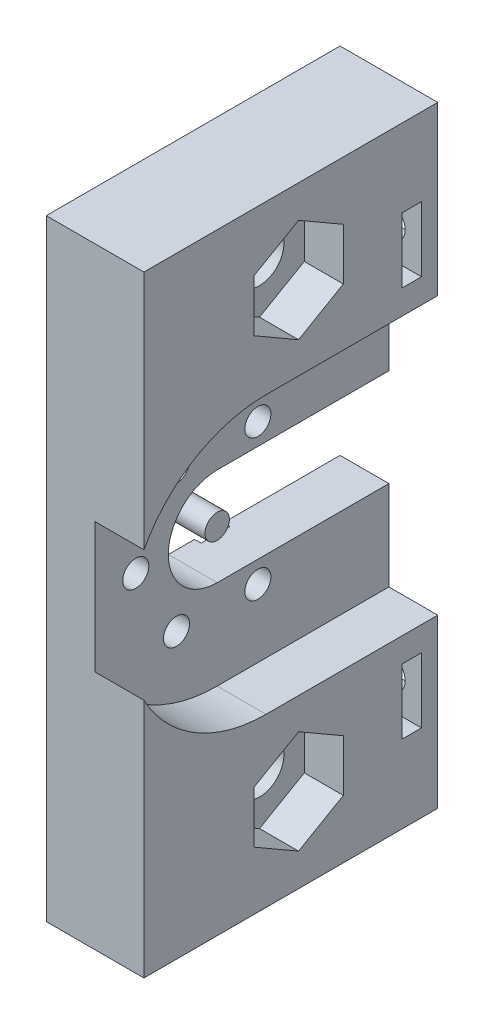
SolidWorks part; units mm, degrees
ref_plane "正面" through (0, 0, 0) normal (1, 0, 0) x (0, 1, 0)
ref_plane "平面" through (0, 0, 0) normal (0, 0, 1) x (0, 1, 0)
ref_plane "右側面" through (0, 0, 0) normal (0, 1, 0) x (-1, 0, 0)
sketch "ｽｹｯﾁ2" plane through (0, 0, 0) normal (1, 0, 0) x (0, 1, 0)
  line L5 (20, -7.5) -> (-20, -7.5)
  line L6 (20, -7.5) -> (20, 7.5)
  line L7 (20, 7.5) -> (-20, 7.5)
  line L8 (-20, -7.5) -> (-20, 7.5)
  line L9 (20, -7.5) -> (-20, 7.5) construction
  line L10 (20, 7.5) -> (-20, -7.5) construction
  point P0 (0, 0)
  dimension "D1" = 40
  dimension "D2" = 15
extrude "ﾎﾞｽ - 押し出し5" add sketch "ｽｹｯﾁ2" along normal mid plane 6
sketch "ｽｹｯﾁ10" plane through (3, 0, 0) normal (1, 0, 0) x (0, 1, 0)
  circle A0 centre (0, 0) radius 5 construction
  circle A1 centre (-4.3301, 2.5) radius 0.8
  circle A2 centre (4.3301, -2.5) radius 0.8
  circle A3 centre (0, 5) radius 0.8
  circle A4 centre (4.3301, 2.5) radius 0.8
  circle A5 centre (-4.3301, -2.5) radius 0.8
  dimension "D1" = 10
  dimension "D2" = 1.6
  dimension "D3" = 1.6
  dimension "D4" = 1.6
  dimension "D6" = 1.6
  dimension "D9" = 1.6
  dimension "D5" = 60
  dimension "D7" = 60
  dimension "D8" = 60
  dimension "D10" = 60
extrude "ｶｯﾄ - 押し出し2" cut sketch "ｽｹｯﾁ10" against normal through all contours A2 | A4 | A3 | A1 | A5
sketch "ｽｹｯﾁ11" plane through (3, 0, 0) normal (1, 0, 0) x (0, 1, 0)
  line L0 (-3, 0) -> (-3, -7.5)
  line L1 (20, -7.5) -> (-20, -7.5) construction
  line L2 (-3, -7.5) -> (3, -7.5)
  line L3 (3, -7.5) -> (3, 0)
  line L4 (3, 0) -> (-3, 0)
  circle A0 centre (0, 0) radius 5 construction
  circle A1 centre (0, 0) radius 3
  line M11 (-20, -7.5) -> (20, -7.5)
  dimension "D1" = 2
extrude "ｶｯﾄ - 押し出し3" cut sketch "ｽｹｯﾁ11" against normal through all contours A1 L0 L3 M11 | L4 A1 | L4 A1
sketch "ｽｹｯﾁ12" plane through (3, 0, 0) normal (1, 0, 0) x (0, 1, 0)
  circle A0 centre (0, 0) radius 8.5
  dimension "D1" = 17
extrude "ｶｯﾄ - 押し出し4" cut sketch "ｽｹｯﾁ12" against normal blind 3
sketch "ｽｹｯﾁ13" plane through (-3, 0, 0) normal (-1, 0, 0) x (0, -1, 0)
  circle A0 centre (0, 0) radius 5 construction
  circle A1 centre (-4.3301, -2.5) radius 1.6
  circle A2 centre (-4.3301, 2.5) radius 1.6
  circle A3 centre (0, 5) radius 1.6
  circle A4 centre (4.3301, 2.5) radius 1.6
  circle A5 centre (4.3301, -2.5) radius 1.6
  dimension "D1" = 3.2
  dimension "D2" = 3.2
  dimension "D3" = 3.2
  dimension "D4" = 3.2
  dimension "D5" = 3.2
  dimension "D6" = 120
  dimension "D7" = 60
  dimension "D8" = 60
extrude "ｶｯﾄ - 押し出し5" cut sketch "ｽｹｯﾁ13" against normal blind 0.4
sketch "ｽｹｯﾁ15" plane through (0, 0, 0) normal (1, 0, 0) x (0, 1, 0)
  circle A0 centre (0, 0) radius 0.75
  dimension "D1" = 1.5
extrude "ﾎﾞｽ - 押し出し6" add sketch "ｽｹｯﾁ15" against normal blind 3 separate body contours A0
sketch "ｽｹｯﾁ16" plane through (-3, 0, 0) normal (-1, 0, 0) x (0, -1, 0)
  line L0 (0, 0) -> (-23.3043, 0) construction
  circle A1 centre (0, 0) radius 3.25 construction
  circle A2 centre (-13.6038, -2) radius 10.5 construction
  circle A3 centre (13.6038, -2) radius 10.5 construction
  circle A4 centre (-13.6038, -2) radius 1.5
  circle A5 centre (13.6038, -2) radius 1.5
  dimension "D1" = 6.5
  dimension "D2" = 21
  dimension "D3" = 21
  dimension "D4" = 3
  dimension "D5" = 3
  dimension "D6" = 2
  dimension "D7" = 2
extrude "ｶｯﾄ - 押し出し6" cut sketch "ｽｹｯﾁ16" against normal through all contours A4 | A5
sketch "ｽｹｯﾁ18" plane through (-3, 0, 0) normal (-1, 0, 0) x (0, -1, 0)
  line L0 (0, 0) -> (-21.0487, 0) construction
  circle A0 centre (0, 0) radius 13.75 construction
  circle A1 centre (-13.6038, -2) radius 2.05
  circle A2 centre (13.6038, -2) radius 2.05
  dimension "D1" = 4.1
  dimension "D2" = 4.1
  dimension "D3" = 2
extrude "ｶｯﾄ - 押し出し8" cut sketch "ｽｹｯﾁ18" against normal blind 1
sketch "ｽｹｯﾁ19" plane through (3, 0, 0) normal (1, 0, 0) x (0, 1, 0)
  line L0 (0, 0) -> (2.6086, 0) construction
  line L1 (-10.4283, -2) -> (-12.0161, 0.75)
  line L2 (-12.0161, 0.75) -> (-15.1915, 0.75)
  line L3 (-15.1915, 0.75) -> (-16.7792, -2)
  line L4 (-16.7792, -2) -> (-15.1915, -4.75)
  line L5 (-15.1915, -4.75) -> (-12.0161, -4.75)
  line L6 (-12.0161, -4.75) -> (-10.4283, -2)
  line L7 (15.1915, 0.75) -> (12.0161, 0.75)
  line L8 (12.0161, 0.75) -> (10.4283, -2)
  line L9 (10.4283, -2) -> (12.0161, -4.75)
  line L10 (12.0161, -4.75) -> (15.1915, -4.75)
  line L11 (15.1915, -4.75) -> (16.7792, -2)
  line L12 (16.7792, -2) -> (15.1915, 0.75)
  circle A0 centre (0, 0) radius 13.75 construction
  circle A1 centre (-13.6038, -2) radius 2.75 construction
  circle A2 centre (13.6038, -2) radius 2.75 construction
  dimension "D1" = 5.5
  dimension "D2" = 5.5
  dimension "D3" = 2
  dimension "D4" = 2
extrude "ｶｯﾄ - 押し出し10" cut sketch "ｽｹｯﾁ19" against normal blind 2.4 contours L11 L12 L7 L8 L9 L10 | L1 L2 L3 L4 L5 L6
sketch "ｽｹｯﾁ21" plane through (3, 0, 0) normal (1, 0, 0) x (0, 1, 0)
  line L0 (0, 0) -> (-5.9571, 0) construction
  line L1 (-13.6038, -2) -> (-13.6038, -7.5) construction
  line L2 (20, -7.5) -> (-20, -7.5) construction
  circle A0 centre (0, 0) radius 3.25 construction
  circle A1 centre (-13.6038, -2) radius 10.5 construction
  circle A2 centre (-13.6038, -2) radius 11.75 construction
  circle A3 centre (13.6038, -2) radius 10.5 construction
  circle A4 centre (13.6038, -2) radius 11.75 construction
  dimension "D1" = 6.5
  dimension "D2" = 21
  dimension "D4" = 23.5
  dimension "D6" = 21
  dimension "D8" = 23.5
  dimension "D3" = 2
  dimension "D5" = 5.5
  dimension "D7" = 2
sketch "ｽｹｯﾁ23" plane through (0, 0, -7.5) normal (0, 0, -1) x (1, 0, 0)
  line L0 (-3, -3) -> (0, -3) construction
  line L6 (-3, 4.0776) -> (-3, 3)
  line L7 (-3, 3) -> (0, 3)
  line L8 (0, 4.0776) -> (0, 3)
  line L9 (-3, -3) -> (0, -3)
  line L10 (-3, -3) -> (-3, -4)
  line L12 (0, -3) -> (0, -4)
  line L13 (0, 4.0776) -> (3, 4.0776)
  line L15 (3, -4) -> (3, -20)
  line L16 (3, -20) -> (-3, -20)
  line L17 (-3, -4) -> (-3, -20)
  line L18 (3, 20) -> (-3, 20)
  line L19 (3, 20) -> (3, 4.0776)
  line L21 (-3, 20) -> (-3, 4.0776)
  line L22 (3, -4) -> (0, -4)
extrude "ﾎﾞｽ - 押し出し7" add sketch "ｽｹｯﾁ23" along normal blind 3.05
sketch "ｽｹｯﾁ22" plane through (3, 0, 0) normal (1, 0, 0) x (0, 1, 0)
  line L0 (-13.6038, -2) -> (-13.6038, -11.75)
  line L1 (-17.1626, -10.55) -> (-10.7729, -10.55) construction
  line L2 (-17.1626, -10.55) -> (-17.1626, -11.75) construction
  line L3 (-17.1626, -11.75) -> (-10.7729, -11.75) construction
  line L4 (-10.7729, -10.55) -> (-10.7729, -11.75) construction
  line L5 (-4.0776, -10.55) -> (-20, -10.55) construction
  line L6 (-13.6038, -11.75) -> (-13.6038, -13.75)
  circle A0 centre (-13.6038, -2) radius 11.75 construction
  dimension "D1" = 1.2
sketch "ｽｹｯﾁ24" plane through (0, -4.0776, 0) normal (0, 1, 0) x (-1, 0, 0)
  line L1 (-3, -7.5) -> (0, -7.5)
  line L2 (-3, -7.5) -> (-3, -10.55)
  line L3 (-3, -10.55) -> (0, -10.55)
  line L4 (0, -7.5) -> (0, -10.55)
extrude "ﾎﾞｽ - 押し出し8" add sketch "ｽｹｯﾁ24" along normal blind 1.08
sketch "ｽｹｯﾁ25" plane through (0, 4, 0) normal (0, -1, 0) x (1, 0, 0)
  line L1 (0, -7.5) -> (3, -7.5)
  line L2 (0, -7.5) -> (0, -10.55)
  line L3 (0, -10.55) -> (3, -10.55)
  line L4 (3, -7.5) -> (3, -10.55)
extrude "ﾎﾞｽ - 押し出し9" add sketch "ｽｹｯﾁ25" along normal blind 1
sketch "ｽｹｯﾁ26" plane through (3, 0, 0) normal (1, 0, 0) x (0, 1, 0)
  line L0 (20, -10.55) -> (3, -10.55) construction
  line L1 (-8.5, 0) -> (8.5, 0)
  line L2 (-8.5, 0) -> (-8.5, -10.55)
  line L3 (-8.5, -10.55) -> (8.5, -10.55)
  line L4 (8.5, 0) -> (8.5, -10.55)
  circle A0 centre (0, 0) radius 8.5
  dimension "D1" = 17
extrude "ｶｯﾄ - 押し出し11" cut sketch "ｽｹｯﾁ26" against normal blind 3 contours A0 | L2 L1 L4 L3
sketch "ｽｹｯﾁ28" plane through (3, 0, 0) normal (1, 0, 0) x (0, 1, 0)
  line L0 (-8.5, -10.55) -> (-20, -10.55) construction
  line L1 (-20, 7.5) -> (-18.7792, 7.5)
  line L2 (-20, 7.5) -> (-20, -10.55)
  line L3 (-20, -10.55) -> (-18.7792, -10.55)
  line L4 (-18.7792, 7.5) -> (-18.7792, -10.55)
  line L5 (20, -10.55) -> (8.5, -10.55) construction
  line L6 (20, 7.5) -> (18.7792, 7.5)
  line L7 (20, 7.5) -> (20, -10.55)
  line L8 (20, -10.55) -> (18.7792, -10.55)
  line L9 (18.7792, 7.5) -> (18.7792, -10.55)
  dimension "D1" = 2
  dimension "D2" = 2
extrude "ｶｯﾄ - 押し出し12" cut sketch "ｽｹｯﾁ28" against normal through all
sketch "ｽｹｯﾁ29" plane through (3, 0, 0) normal (1, 0, 0) x (0, 1, 0)
  line L0 (-8.5, -10.55) -> (-18.7792, -10.55) construction
  line L1 (-14, -8.35) -> (-10, -8.35)
  line L2 (-14, -8.35) -> (-14, -9.55)
  line L3 (-14, -9.55) -> (-10, -9.55)
  line L4 (-10, -8.35) -> (-10, -9.55)
  line L5 (-8.5, 0) -> (-8.5, -10.55) construction
  line L6 (0, 0) -> (0, -4.2645) construction
  line L7 (14, -9.55) -> (10, -9.55)
  line L8 (10, -8.35) -> (10, -9.55)
  line L9 (14, -8.35) -> (10, -8.35)
  line L10 (14, -8.35) -> (14, -9.55)
  dimension "D1" = 1
  dimension "D2" = 4
  dimension "D3" = 1.5
  dimension "D4" = 1.2
extrude "ｶｯﾄ - 押し出し13" cut sketch "ｽｹｯﾁ29" against normal blind 4
sketch "ｽｹｯﾁ30" plane through (0, 0, -9.55) normal (0, 0, 1) x (1, 0, 0)
  line L0 (3, -10) -> (-1, -14) construction
  line L1 (-1, -10) -> (3, -14) construction
  line L2 (0, 0) -> (3, 0) construction
  line L3 (3, -3.25) -> (3, 3.25) construction
  circle A0 centre (1, -12) radius 1
  circle A1 centre (1, 12) radius 1
  dimension "D1" = 2
extrude "ｶｯﾄ - 押し出し14" cut sketch "ｽｹｯﾁ30" against normal through all
